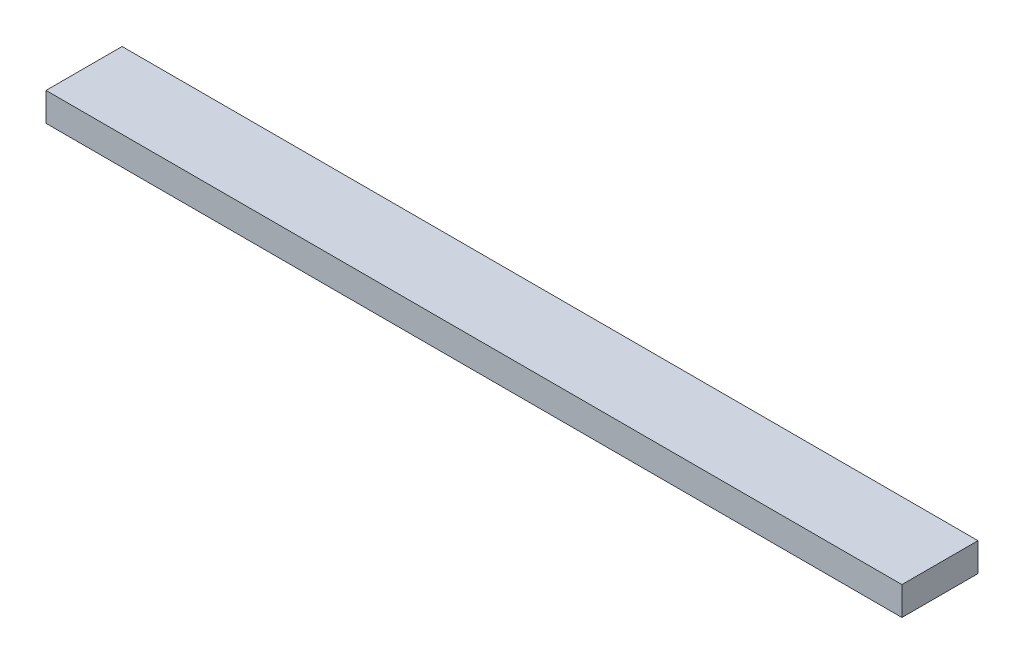
SolidWorks part; units mm, degrees
ref_plane "Front Plane" through (0, 0, 0) normal (0, 0, 1) x (1, 0, 0)
ref_plane "Top Plane" through (0, 0, 0) normal (0, 1, 0) x (1, 0, 0)
ref_plane "Right Plane" through (0, 0, 0) normal (1, 0, 0) x (0, 0, -1)
sketch "Sketch1" plane through (0, 0, 0) normal (0, 1, 0) x (1, 0, 0)
  line L1 (-9.7834, 4.4841) -> (-99.7834, 4.4841)
  line L2 (-9.7834, 4.4841) -> (-9.7834, 12.4841)
  line L3 (-9.7834, 12.4841) -> (-99.7834, 12.4841)
  line L4 (-99.7834, 4.4841) -> (-99.7834, 12.4841)
  dimension "D1" = 8
  dimension "D2" = 90
extrude "Boss-Extrude1" add sketch "Sketch1" along normal blind 3
